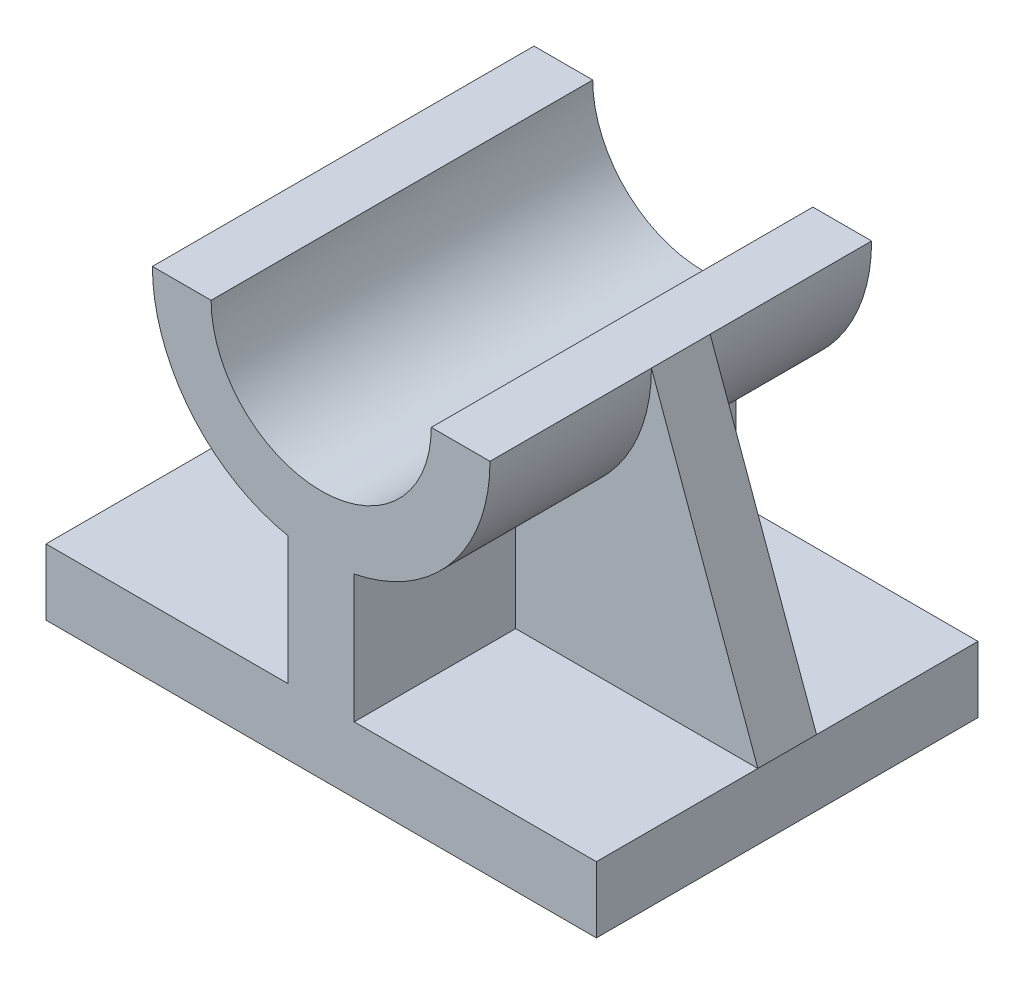
SolidWorks part; units mm, degrees
ref_plane "Front Plane" through (0, 0, 0) normal (0, 0, 1) x (1, 0, 0)
ref_plane "Top Plane" through (0, 0, 0) normal (0, 1, 0) x (1, 0, 0)
ref_plane "Right Plane" through (0, 0, 0) normal (1, 0, 0) x (0, 0, -1)
sketch "Sketch1" plane through (0, 0, 0) normal (0, 1, 0) x (1, 0, 0)
  line L1 (-37.5, -26) -> (37.5, -26)
  line L2 (-37.5, -26) -> (-37.5, 26)
  line L3 (-37.5, 26) -> (37.5, 26)
  line L4 (37.5, -26) -> (37.5, 26)
  line L5 (-37.5, -26) -> (37.5, 26) construction
  line L6 (-37.5, 26) -> (37.5, -26) construction
  point P0 (0, 0)
  dimension "D1" = 75
  dimension "D2" = 52
extrude "Boss-Extrude1" add sketch "Sketch1" along normal blind 9
sketch "Sketch2" plane through (0, 0, 26) normal (0, 0, 1) x (1, 0, 0)
  line L0 (-37.5, 9) -> (37.5, 9) construction
  line L1 (-4.5, 9) -> (4.5, 9)
  line L2 (-4.5, 9) -> (-4.5, 34.6909)
  line L4 (4.5, 9) -> (4.5, 34.6909)
  line L5 (-23, 49) -> (-15, 49)
  line L7 (15, 49) -> (23, 49)
  arc A0 (-15, 49) -> (15, 49) centre (0, 49) ccw
  arc A1 (-23, 49) -> (23, 49) centre (0, 49) ccw
  point P13 (0, 49)
  dimension "D2" = 33
  dimension "D3" = 9
extrude "Boss-Extrude2" add sketch "Sketch2" against normal blind 52 contours L4 A1 L7 A0 | L5 A1 L2 A0 | L2 A1 L4 A0 | A1 L2 L0 L4
ref_plane "Plane1" through (23, 49, 26) normal (0, 0, 1) x (1, 0, 0)
sketch "Sketch3" plane through (0, 0, 0) normal (0, 0, 1) x (1, 0, 0)
  line L0 (23, 49) -> (37.5, 9)
rib "Rib1" sketch "Sketch3" sketch "Sketch3" thickness 8 extrusion direction parallel to sketch draft on no parameters "D1"=8
